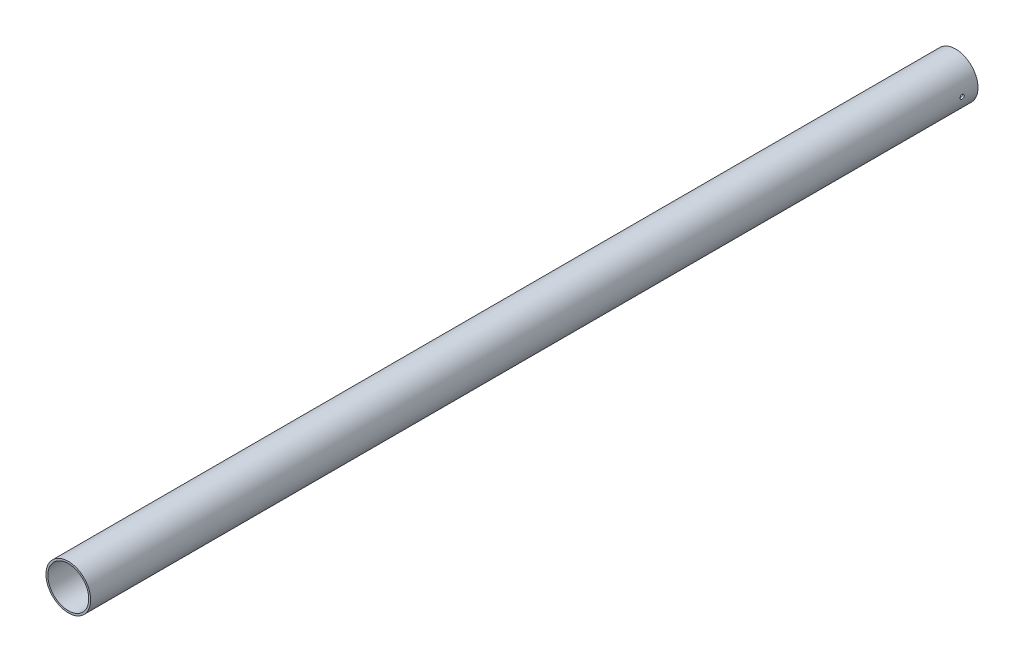
SolidWorks part; units mm, degrees
material "PC High Viscosity"
ref_plane "Front Plane" through (0, 0, 0) normal (0, 0, 1) x (1, 0, 0)
ref_plane "Top Plane" through (0, 0, 0) normal (0, 1, 0) x (1, 0, 0)
ref_plane "Right Plane" through (0, 0, 0) normal (1, 0, 0) x (0, 0, -1)
sketch "Sketch1" plane through (0, 0, 0) normal (0, 0, 1) x (1, 0, 0)
  circle A0 centre (0, 0) radius 12.7
  circle A1 centre (0, 0) radius 11.6205
  dimension "D1" = 25.4
  dimension "D2" = 23.241
extrude "Boss-Extrude1" add sketch "Sketch1" along normal blind 504.28
hole_wizard "M2 Clearance Hole1" positions "Sketch2" profile "Sketch3" hole size "M2" standard "ANSI Metric"
sketch "Sketch2" plane through (0, 0, 0) normal (1, 0, 0) x (0, 0, -1)
  line L1 (0, -12.7) -> (0, 12.7) construction
  point P0 (-9, 0)
  dimension "D1" = 9
sketch "Sketch3" plane through (0, 0, 9) normal (0, 1, 0) x (0, 0, 1)
  line L0 (0, 0) -> (0, 12.7)
  line L1 (0, 12.7) -> (1.2, 12.7)
  line L2 (1.2, 12.7) -> (1.2, 0)
  line L5 (1.2, 0) -> (0, 0)
  line L11 (0, -6.35) -> (0, 107.95) construction
  dimension "Thru Hole Dia." = 2.4
  dimension "Thru Hole Depth" = 12.7
mirror "Mirror1" about plane through (0, 0, 0) normal (1, 0, 0) of "M2 Clearance Hole1"
